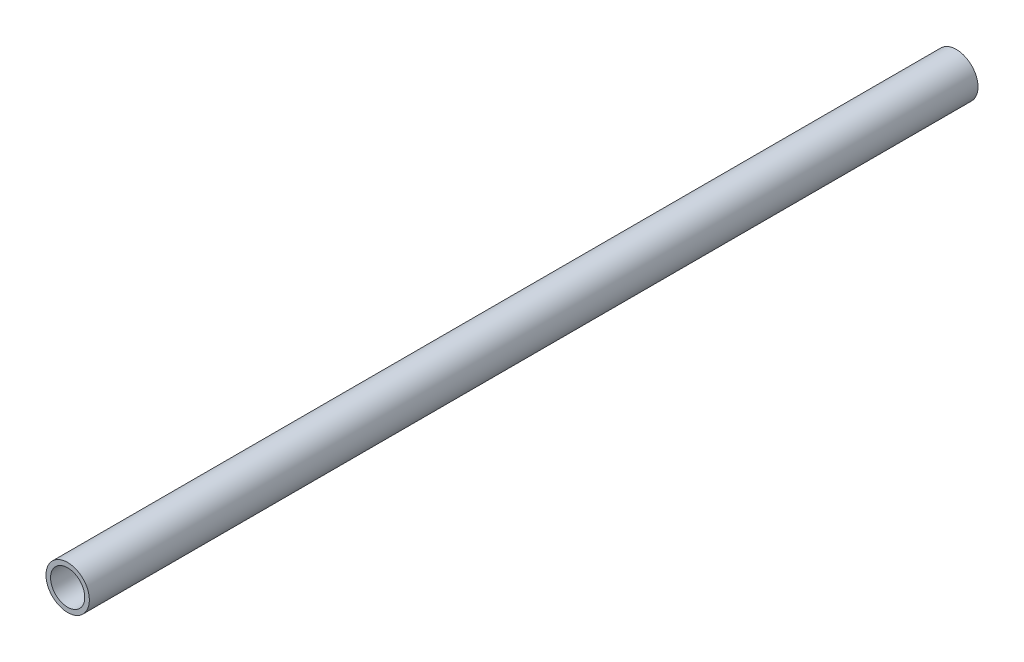
SolidWorks part; units mm, degrees
ref_plane "Front Plane" through (0, 0, 0) normal (0, 0, 1) x (1, 0, 0)
ref_plane "Top Plane" through (0, 0, 0) normal (0, 1, 0) x (1, 0, 0)
ref_plane "Right Plane" through (0, 0, 0) normal (1, 0, 0) x (0, 0, -1)
sketch "Sketch1" plane through (0, 0, 0) normal (0, 0, 1) x (1, 0, 0)
  circle A0 centre (0, 0) radius 3.175
  circle A1 centre (0, 0) radius 2.5
extrude "Boss-Extrude1" add sketch "Sketch1" along normal blind 130
